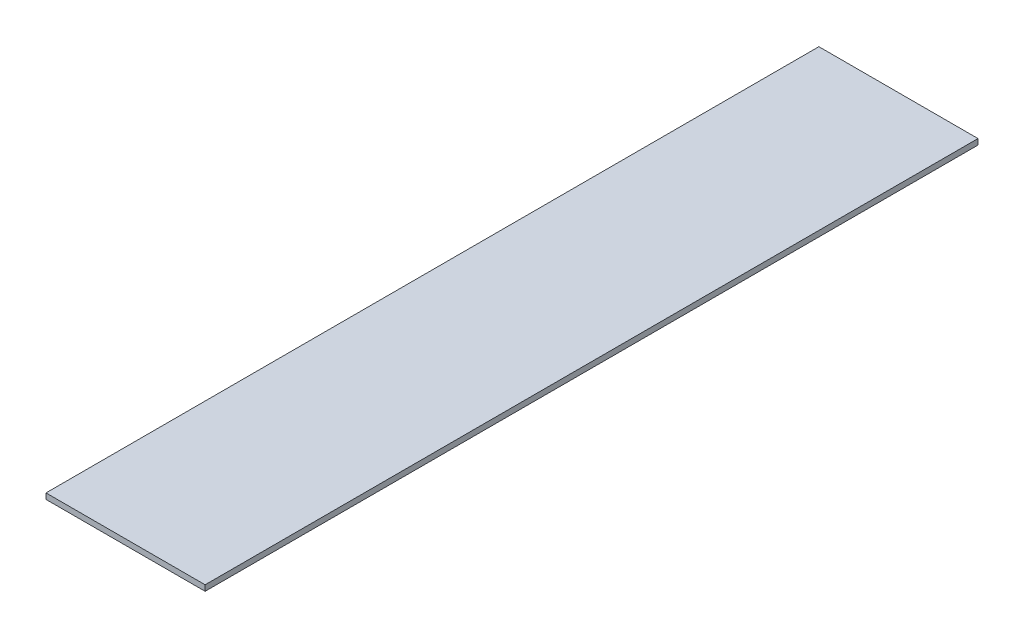
SolidWorks part; units mm, degrees
ref_plane "Front Plane" through (0, 0, 0) normal (0, 0, 1) x (1, 0, 0)
ref_plane "Top Plane" through (0, 0, 0) normal (0, 1, 0) x (1, 0, 0)
ref_plane "Right Plane" through (0, 0, 0) normal (1, 0, 0) x (0, 0, -1)
other "Configuration Table"
sketch "Sketch1" plane through (0, 0, 0) normal (0, 0, 1) x (1, 0, 0)
  line L1 (-70, 255) -> (70, 255)
  line L2 (-70, 255) -> (-70, 260)
  line L3 (-70, 260) -> (70, 260)
  line L4 (70, 255) -> (70, 260)
extrude "KAP_PC_kapak_gecmeli_1" add sketch "Sketch1" against normal blind 680 from offset 20 separate body
